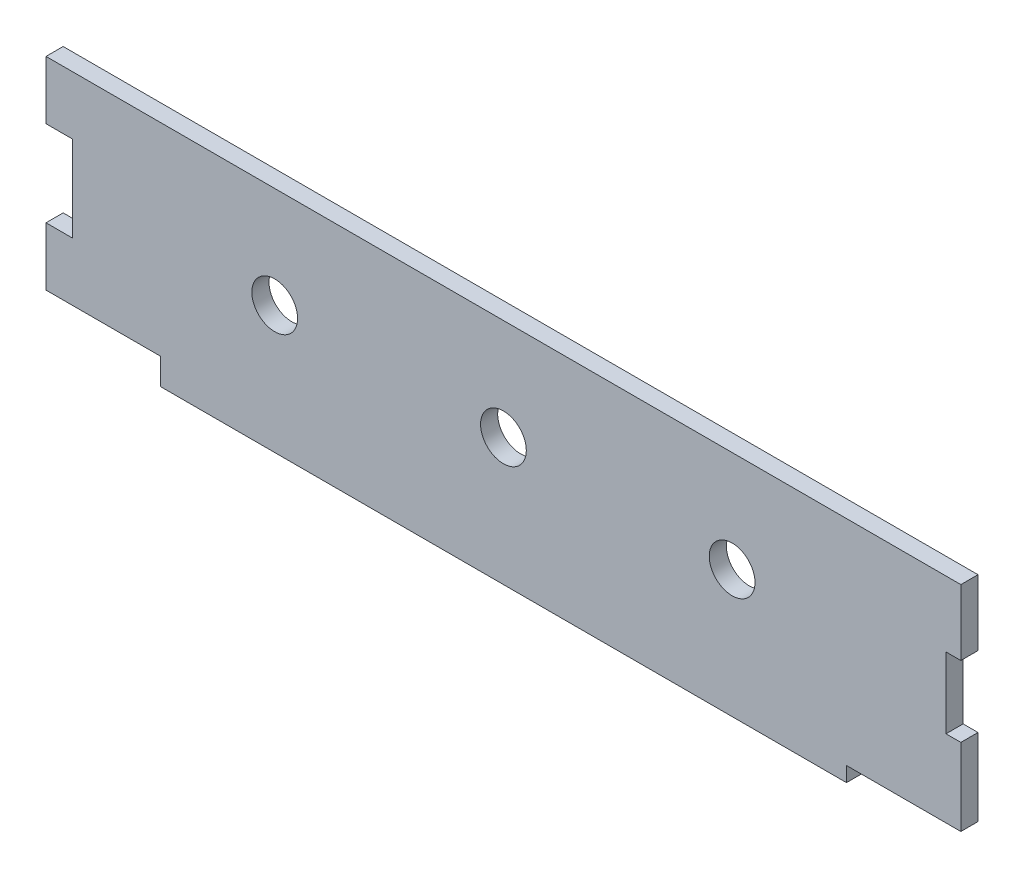
SolidWorks part; units mm, degrees
ref_plane "Alzado" through (0, 0, 0) normal (0, 0, 1) x (1, 0, 0)
ref_plane "Planta" through (0, 0, 0) normal (0, 1, 0) x (1, 0, 0)
ref_plane "Vista lateral" through (0, 0, 0) normal (1, 0, 0) x (0, 0, -1)
sketch "Croquis1" plane through (0, 0, 0) normal (0, 0, 1) x (1, 0, 0)
  line L0 (-40, 8.85) -> (40, 8.85)
  line L1 (40, 8.85) -> (40, 3.1)
  line L2 (40, 3.1) -> (38.7, 3.1)
  line L3 (38.7, 3.1) -> (38.7, -3.1)
  line L4 (38.7, -3.1) -> (40, -3.1)
  line L5 (40, -3.1) -> (40, -9.85)
  line L6 (40, -9.85) -> (30, -9.85)
  line L7 (30, -9.85) -> (30, -11.15)
  line L8 (30, -11.15) -> (-30, -11.15)
  line L9 (-30, -11.15) -> (-30, -8.85)
  line L10 (-30, -8.85) -> (-40, -8.85)
  line L11 (-40, -8.85) -> (-40, -3.75)
  line L12 (-40, -3.75) -> (-37.7, -3.75)
  line L13 (-37.7, -3.75) -> (-37.7, 3.75)
  line L14 (-37.7, 3.75) -> (-40, 3.75)
  line L15 (-40, 3.75) -> (-40, 8.85)
  line L16 (38.7, 0) -> (-37.7, 0) construction
  circle A0 centre (20, 0) radius 2
  circle A1 centre (0, 0) radius 2
  circle A2 centre (-20, 0) radius 2
  point P16 (-37.7, 0)
  point P18 (38.7, 0)
  point P19 (0, 8.85)
  dimension "D9" = 4
  dimension "D10" = 20
  dimension "D11" = 20
  dimension "D12" = 20
  dimension "D1" = 80
  dimension "D2" = 10
  dimension "D3" = 10
  dimension "D4" = 20
  dimension "D5" = 7.5
  dimension "D6" = 6.2
  dimension "D7" = 2.3
  dimension "D8" = 1.3
extrude "Saliente-Extruir1" add sketch "Croquis1" along normal blind 1.5
